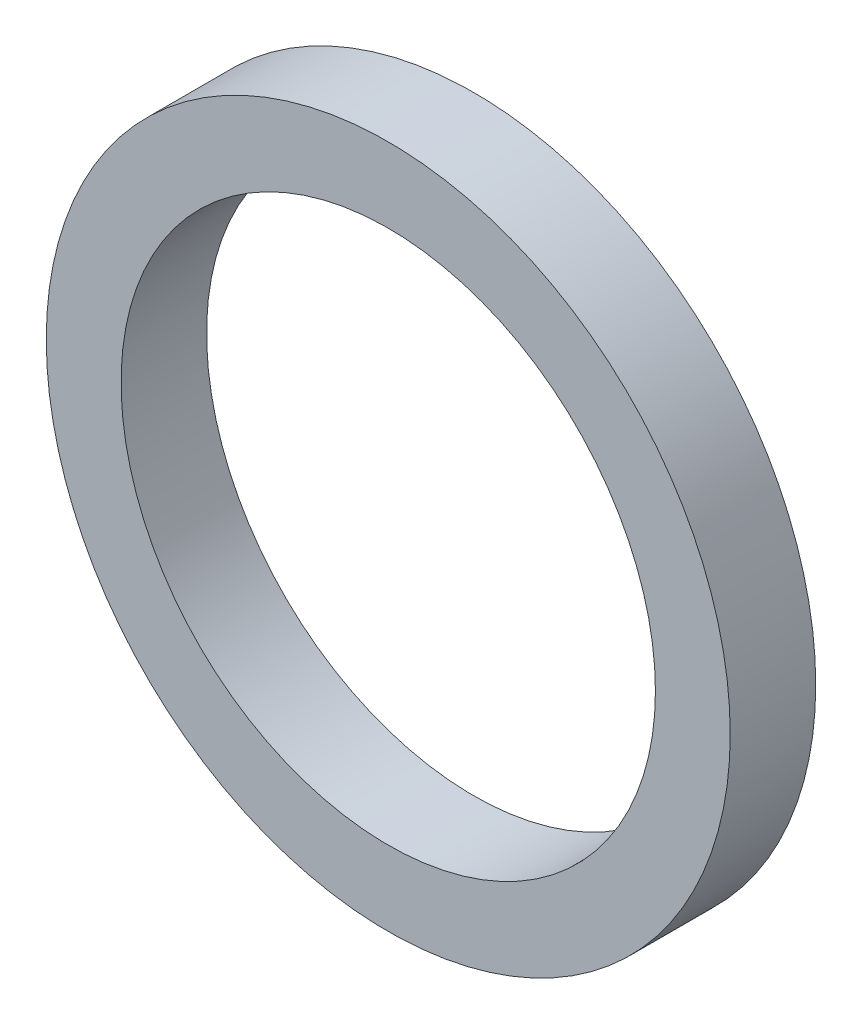
SolidWorks part; units mm, degrees
material "合金钢 (SS)"
ref_plane "前视基准面" through (0, 0, 0) normal (0, 0, 1) x (1, 0, 0)
ref_plane "上视基准面" through (0, 0, 0) normal (0, 1, 0) x (1, 0, 0)
ref_plane "右视基准面" through (0, 0, 0) normal (1, 0, 0) x (0, 0, -1)
sketch "草图1" plane through (0, 0, 0) normal (0, 0, 1) x (1, 0, 0)
  circle A0 centre (0, 0) radius 12.5
  circle A1 centre (0, 0) radius 16
  dimension "D1" = 25
  dimension "D2" = 32
extrude "凸台-拉伸1" add sketch "草图1" along normal mid plane 4
